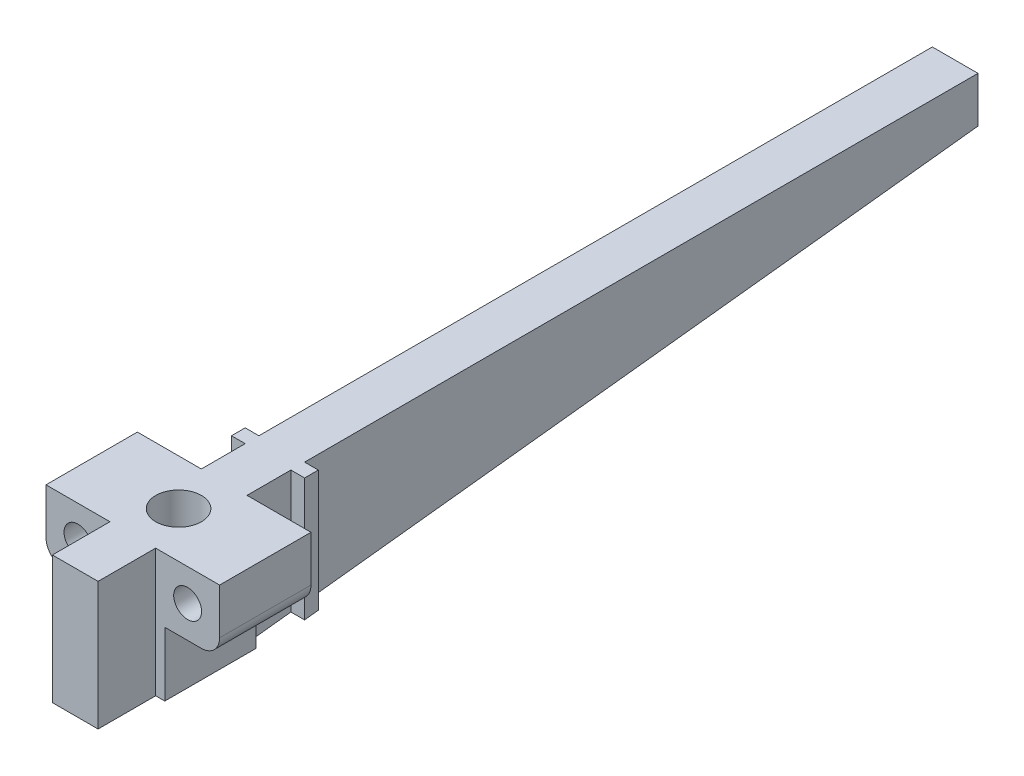
SolidWorks part; units mm, degrees
ref_plane "前视基准面" through (0, 0, 0) normal (0, 0, 1) x (1, 0, 0)
ref_plane "上视基准面" through (0, 0, 0) normal (0, 1, 0) x (1, 0, 0)
ref_plane "右视基准面" through (0, 0, 0) normal (1, 0, 0) x (0, 0, -1)
other "Configuration Table"
sketch "草图1" plane through (0, 0, 0) normal (0, 0, 1) x (1, 0, 0)
  line L0 (-4.6095, 6.3014) -> (-4.6095, 1.3014)
  line L5 (-2.6095, -0.6986) -> (1.3905, -0.6986)
  line L6 (1.3905, -0.6986) -> (1.3905, -7.6986)
  line L7 (1.3905, -7.6986) -> (8.3905, -7.6986)
  line L8 (8.3905, -7.6986) -> (8.3905, -0.6986)
  line L9 (8.3905, -0.6986) -> (12.3905, -0.6986)
  line L10 (14.3905, 1.3014) -> (14.3905, 6.3014)
  line L11 (14.3905, 6.3014) -> (-4.6095, 6.3014)
  arc A0 (-4.6095, 1.3014) -> (-2.6095, -0.6986) centre (-2.6095, 1.3014) ccw
  arc A1 (12.3905, -0.6986) -> (14.3905, 1.3014) centre (12.3905, 1.3014) ccw
  circle A2 centre (10.8905, 2.8014) radius 1.525
  circle A3 centre (-1.1095, 2.8014) radius 1.525
extrude "凸台-拉伸1" add sketch "草图1" along normal blind 10
ref_plane "基准面1" through (4.8905, 0, 0) normal (1, 0, 0) x (0, 0, -1)
sketch "草图3" plane through (4.8905, 0, 0) normal (1, 0, 0) x (0, 0, -1)
  line L0 (0, 6.3014) -> (80, 6.3014)
  line L1 (80, 6.3014) -> (80, 1.3014)
  line L2 (80, 1.3014) -> (0, -7.6986)
  line L3 (0, 6.3014) -> (0, -7.6986)
  dimension "D1" = 80
  dimension "D2" = 5
extrude "凸台-拉伸2" add sketch "草图3" along normal blind 2.5 and the other way blind 2.5
sketch "草图4" plane through (0, 0, 10) normal (0, 0, 1) x (1, 0, 0)
  line L0 (4.8905, 6.3014) -> (4.8905, 8.8738) construction
  line L2 (14.3905, 6.3014) -> (-4.6095, 6.3014) construction
  line L3 (2.3905, 6.3014) -> (7.3905, 6.3014)
  line L4 (2.3905, 6.3014) -> (2.3905, -7.6986)
  line L5 (2.3905, -7.6986) -> (7.3905, -7.6986)
  line L6 (7.3905, 6.3014) -> (7.3905, -7.6986)
  line L7 (1.3905, -7.6986) -> (8.3905, -7.6986) construction
  point P6 (4.8905, 6.3014)
  point P9 (4.8905, 6.3014)
  dimension "D1" = 5
extrude "凸台-拉伸3" add sketch "草图4" along normal blind 6.3
sketch "草图5" plane through (0, 6.3014, 0) normal (0, 1, 0) x (1, 0, 0)
  line L0 (-4.6095, -5) -> (49995.3905, -5) construction
  line L1 (-4.6095, -10) -> (-4.6095, 0) construction
  line L2 (4.8905, -20) -> (4.8905, 49980) construction
  line L3 (7.3905, -16.3) -> (2.3905, -16.3) construction
  circle A0 centre (4.9009, -5) radius 2.5
  point P4 (-4.6095, -5)
  point P9 (4.8905, -16.3)
  dimension "D1" = 5
extrude "切除-拉伸1" cut sketch "草图5" against normal up to next
sketch "草图6" plane through (7.3905, 0, 0) normal (1, 0, 0) x (0, 0, -1)
  line L0 (4.8, 6.3014) -> (4.8, -7.1586)
  line L1 (6.3, 6.3014) -> (6.3, -6.9899)
  line L4 (0, 6.3014) -> (0, -7.6986)
  line L5 (0, -7.6986) -> (80, 1.3014)
  line L6 (80, 1.3014) -> (80, 6.3014)
  line L7 (80, 6.3014) -> (0, 6.3014)
  line L8 (0, 6.3014) -> (0, -7.6986)
  line L9 (0, -7.6986) -> (6.3, -6.9899)
  line L11 (6.3, 6.3014) -> (0, 6.3014)
  line M7 (0, -7.6986) -> (80, 1.3014)
  line M9 (80, 6.3014) -> (0, 6.3014)
  dimension "D2" = 1.5
  dimension "D3" = 6.3
  dimension "D1" = 0
extrude "凸台-拉伸5" add sketch "草图6" along normal blind 1.5 contours L1 L0 M9 M7
mirror "镜向1" about plane through (4.8905, 0, 0) normal (1, 0, 0) of "凸台-拉伸5"
